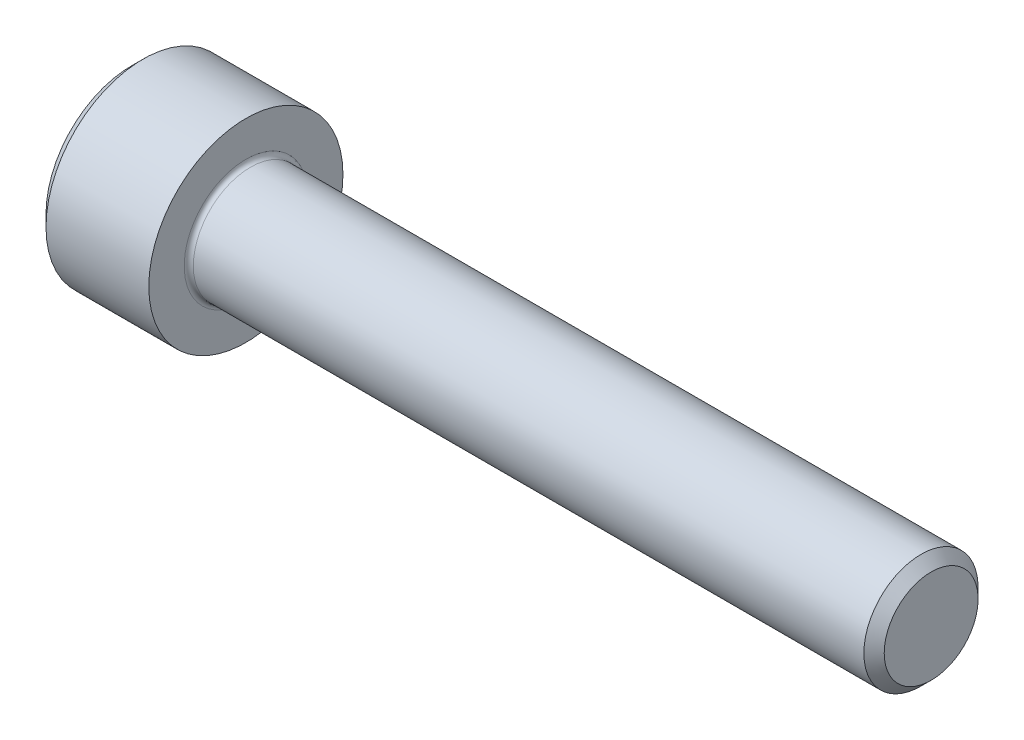
SolidWorks part; units mm, degrees
revolve "Base-Revolve" add sketch "BodySke"
sketch "BodySke" plane through (0, 0, 0) normal (0, 0, 1) x (1, 0, 0)
  line L0 (0, 0) -> (0, 3.75)
  line L1 (0.5, 4.25) -> (5, 4.25)
  line L2 (5, 4.25) -> (5, 2.5)
  line L3 (5, 2.5) -> (34.555, 2.5)
  line L4 (35, 2.055) -> (35, 0)
  line L5 (35, 0) -> (0, 0)
  line L6 (-31.75, 0) -> (127, 0) construction
  line L7 (0, 3.75) -> (0.5, 4.25)
  line L8 (35, 2.055) -> (34.555, 2.5)
  line L9 (0, -3.75) -> (0.5, -4.25) construction
  line L10 (35, -2.055) -> (34.555, -2.5) construction
  line L11 (5.8, 9.525) -> (5.8, 3.175) construction
  line L12 (13, 9.525) -> (13, 3.175) construction
  line L13 (-15, 9.525) -> (-15, 3.175) construction
  dimension "Diameter" = 5
  dimension "Head_ht" = 5
  dimension "Length" = 30
  dimension "Body_ch_ang" = 45
  dimension "Head_dia" = 8.5
  dimension "Head_ch_ang" = 45
  dimension "Minor_dia" = 4.11
  dimension "Advance" = 0.8
  dimension "Thread_nom" = 22
  dimension "Thread_length" = 50
  dimension "Head_ch_ht" = 0.5
cosmetic thread "ThreadCosmetic"
fillet "Fillet1" radius 0.2 1 edges at (5, 0, 2.5)
ref_plane "Plane1" through (0, 0, 0) normal (0, 0, 1) x (1, 0, 0)
ref_plane "Plane2" through (0, 0, 0) normal (0, 1, 0) x (1, 0, 0)
ref_plane "Plane3" through (0, 0, 0) normal (1, 0, 0) x (0, 0, -1)
sketch "Sketch2" plane through (0, 0, 0) normal (0, 0, 1) x (1, 0, 0)
  line L0 (0, 2.042) -> (2.5, 2.042)
  line L1 (2.5, 2.042) -> (3.6789, 0)
  line L2 (-31.75, 0) -> (127, 0) construction
  line L3 (3.6789, 0) -> (0, 0)
  line L4 (0, 0) -> (0, 2.042)
  line L5 (0, 3.75) -> (0, -3.75) construction
  line L6 (0, 0) -> (47.625, 0) construction
  line L7 (5, -4.25) -> (5, 4.25) construction
  dimension "D1" = 2.042
  dimension "D2" = 60
revolve "Hex-PreBroach" cut sketch "Sketch2" angle 360 about L6
sketch "Sketch3" plane through (0, 0, 0) normal (-1, 0, 0) x (0, 0.5, 0.866)
  line L0 (1.1789, 2.042) -> (-1.1789, 2.042)
  line L1 (-1.1789, 2.042) -> (-2.3579, 0)
  line L2 (1.1789, 2.042) -> (2.3579, 0)
  line L3 (1.1789, -2.042) -> (2.3579, 0)
  line L4 (1.1789, -2.042) -> (-1.1789, -2.042)
  line L5 (-1.1789, -2.042) -> (-2.3579, 0)
  dimension "D1" = 2.042
  dimension "D2" = 2.042
  dimension "Hex_size" = 4.084
extrude "Hex" cut sketch "Sketch3" against normal blind 2.5
sketch "Sketch4" plane through (0, 0, 0) normal (-1, 0, 0) x (0, 0, 1)
  line L0 (0, 0) -> (2.3876, 0)
  line L1 (0, 0) -> (6.1484, 3.5498) construction
  line L2 (0, 0) -> (1.1938, 2.0677)
  line L3 (1.9883, 0.576) -> (2.2704, 0.7389)
  line L4 (1.493, 1.4339) -> (1.7751, 1.5968)
  arc A0 (1.9883, 0.576) -> (1.493, 1.4339) centre (0, 0) ccw
  arc A1 (2.3876, 0) -> (2.2704, 0.7389) centre (0, 0) ccw
  arc A2 (1.1938, 2.0677) -> (1.7751, 1.5968) centre (0, 0) cw
  dimension "D1" = 30
  dimension "D2" = 60
  dimension "Spline_p_dim" = 0.9906
  dimension "D3" = 0.4953
extrude "Spline" [suppressed] cut sketch "Sketch4" against normal blind 2.5
pattern_circular "CirPattern1" [suppressed] count 6 every 60
sketch "Sketch5" plane through (0, 0, 0) normal (0, 0, 1) x (1, 0, 0)
  line L0 (-31.75, 0) -> (127, 0) construction
  line L2 (0, 3.75) -> (0, -3.75) construction
  circle A0 centre (2, 0) radius 0.675
  dimension "Drilled_hole_dia" = 1.35
  dimension "Drilled_hole_loc" = 2
extrude "Hole" [suppressed] cut sketch "Sketch5" against normal through all and the other way through all
pattern_circular "Drilled-4" [suppressed] count 2 every 60
pattern_circular "Drilled-6" [suppressed] count 3 every 60
sketch "ThdSchSke" plane through (0, 0, 0) normal (0, 0, 1) x (1, 0, 0)
  line L0 (13, -2.055) -> (12.6884, -2.5)
  line L1 (13, -2.055) -> (13.3116, -2.5)
  line L2 (13.3116, -2.5) -> (13.3116, -3.125)
  line L3 (-3.175, 0) -> (5.1513, 0) construction
  line L5 (13.3116, -3.125) -> (12.6884, -3.125)
  line L6 (12.6884, -3.125) -> (12.6884, -2.5)
  line L7 (0, 3.75) -> (0, -3.75) construction
  dimension "Thread_minor" = 4.11
  dimension "Diameter" = 5
  dimension "Start" = 13
revolve "ThreadSchematic" [suppressed] cut sketch "ThdSchSke" angle 360 about L3
pattern_linear "ThdSchPat" [suppressed]
equation "\"D2@Sketch3\" = \"Hex_size@Sketch3\" / 2"
equation "\"D1@Sketch3\" = \"Hex_size@Sketch3\" / 2"
equation "\"D1@Sketch2\" = \"Hex_size@Sketch3\" / 2"
equation "\"D3@Sketch4\" = \"Spline_p_dim@Sketch4\" / 2"
equation "\"Thread_minor@ThreadCosmetic\"  =  \"Minor_dia@BodySke\""
equation "\"D2@CirPattern1\" = 360 / \"Num_teeth@CirPattern1\""
equation "\"Wall_thickness@Sketch2\" = \"Head_ht@BodySke\" - \"Key_eng@Hex\""
equation "\"Thread_length@ThreadCosmetic\" = ((sgn( (\"Length@BodySke\" - \"Advance@BodySke\" ) - \"Thread_nom@BodySke\" )-1)*( (\"Length@BodySke\" - \"Advance@BodySke\" ) - \"Thread_nom@BodySke\" ))/-2+ \"Thread_nom@BodySke\""
equation "\"Thread_minor@ThdSchSke\" = \"Minor_dia@BodySke\""
equation "\"Diameter@ThdSchSke\" = \"Diameter@BodySke\""
equation "\"Overcut@ThdSchSke\" = \"Diameter@BodySke\" * 1.25"
equation "\"Start@ThdSchSke\" = \"Head_ht@BodySke\" + \"Length@BodySke\" - \"Thread_length@ThreadCosmetic\"  '---Non-countersunk---"
equation "\"Num_threads@ThdSchPat\" = int( \"Thread_length@ThreadCosmetic\" / \"Advance@BodySke\" + 0.999 )  + 1"
equation "\"Advance@ThdSchPat\" = \"Thread_length@ThreadCosmetic\" /  (\"Num_threads@ThdSchPat\" - 1) 'relax it"
equation "\"Num_threads@ThdSchPat\" = \"Num_threads@ThdSchPat\" - sgn( \"Num_threads@ThdSchPat\" - 1) '---chamfered tips only---"
